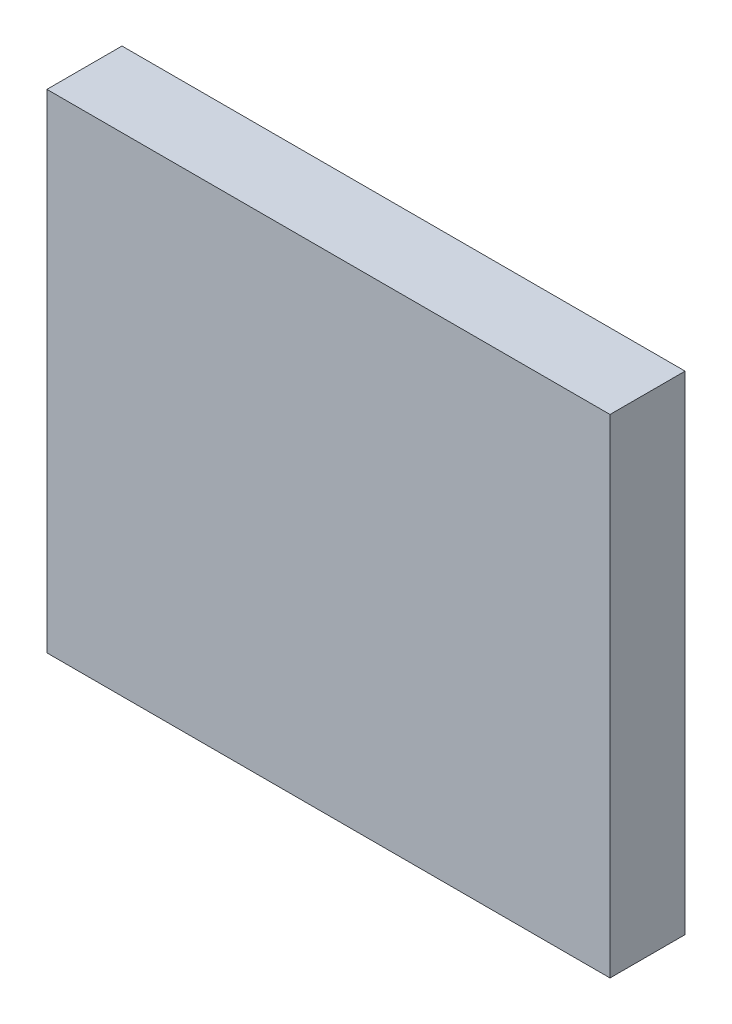
SolidWorks part; units mm, degrees
ref_plane "Plan de face" through (0, 0, 0) normal (0, 0, 1) x (1, 0, 0)
ref_plane "Plan de dessus" through (0, 0, 0) normal (0, 1, 0) x (1, 0, 0)
ref_plane "Plan de droite" through (0, 0, 0) normal (1, 0, 0) x (0, 0, -1)
sketch "Esquisse1" plane through (0, 0, 0) normal (0, 0, 1) x (1, 0, 0)
  line L1 (-47.625, 41.275) -> (47.625, 41.275)
  line L2 (-47.625, 41.275) -> (-47.625, -41.275)
  line L3 (-47.625, -41.275) -> (47.625, -41.275)
  line L4 (47.625, 41.275) -> (47.625, -41.275)
  line L5 (-47.625, 41.275) -> (47.625, -41.275) construction
  line L6 (-47.625, -41.275) -> (47.625, 41.275) construction
  point P0 (0, 0)
  dimension "D1" = 82.55
  dimension "D2" = 95.25
extrude "Boss.-Extru.1" add sketch "Esquisse1" along normal blind 12.7
